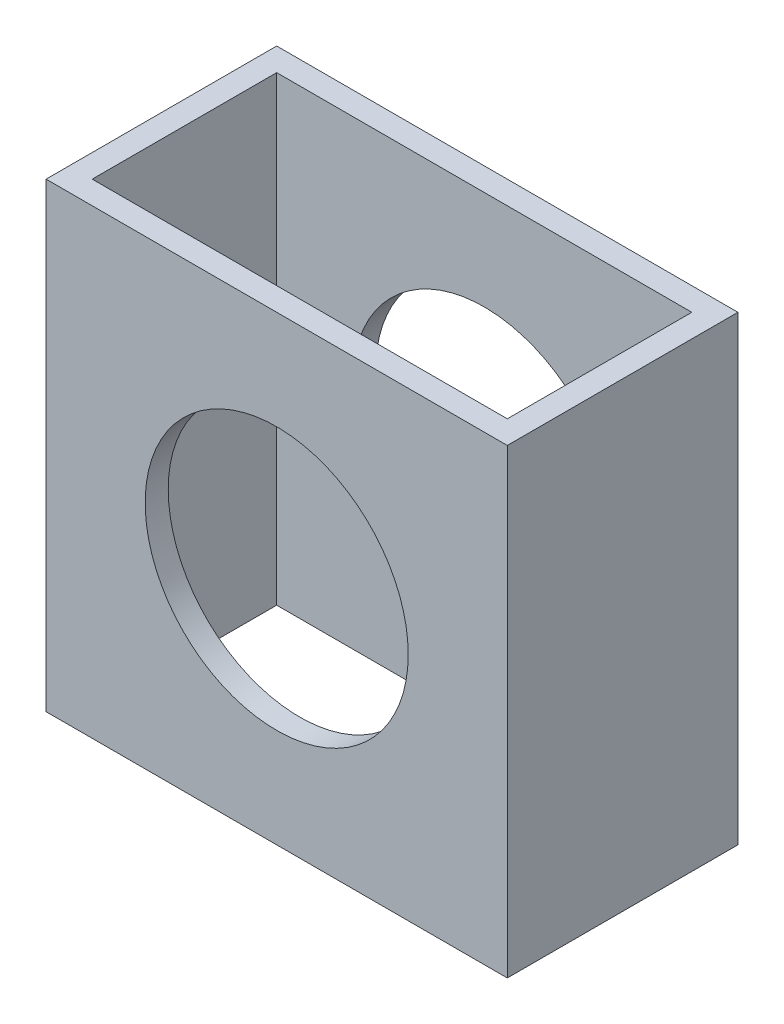
SolidWorks part; units mm, degrees
ref_plane "Front Plane" through (0, 0, 0) normal (0, 0, 1) x (1, 0, 0)
ref_plane "Top Plane" through (0, 0, 0) normal (0, 1, 0) x (1, 0, 0)
ref_plane "Right Plane" through (0, 0, 0) normal (1, 0, 0) x (0, 0, -1)
sketch "Sketch1" plane through (0, 0, 0) normal (1, 0, 0) x (0, 0, -1)
  line L0 (0, 0) -> (0, 50.8)
  dimension "D1" = 50.8
other "Rectangular tube 2IN X 1IN(1)"
ref_plane "Plane1" through (-25.4, 0, -12.7) normal (0, 1, 0) x (0, 0, 1)
sketch "Sketch12" plane through (-25.4, 0, -12.7) normal (0, 1, 0) x (0, 0, 1)
  line L0 (0, 0) -> (0, 50.8)
  line L1 (0, 50.8) -> (25.4, 50.8)
  line L2 (0, 0) -> (25.4, 0)
  line L3 (25.4, 50.8) -> (25.4, 0)
  line L4 (2.54, 48.26) -> (22.86, 48.26)
  line L5 (22.86, 48.26) -> (22.86, 2.54)
  line L6 (2.54, 2.54) -> (22.86, 2.54)
  line L7 (2.54, 2.54) -> (2.54, 48.26)
  line L8 (0, 0) -> (25.4, 50.8) construction
  point P0 (0, 0)
  point P2 (0, 25.4)
  point P4 (0, 0)
  point P6 (12.7, 0)
  point P7 (0, 25.4)
  point P8 (25.4, 25.4)
  point P9 (25.4, 0)
  point P10 (12.7, 50.8)
  point P11 (25.4, 50.8)
  point P12 (0, 50.8)
  point P16 (0, 0)
  point P17 (0, 0)
  point P19 (12.7, 25.4)
  point P20 (25.4, 0)
  point P23 (25.4, 50.8)
  point P26 (0, 50.8)
  dimension "D2" = 25.4
  dimension "D3" = 2.54
  dimension "D1" = 50.8
hole_wizard "1-1/8 Clearance Hole1" positions "Sketch13" profile "Sketch14" hole size "1-1/8" standard "ANSI Inch" end condition through all
sketch "Sketch13" plane through (0, 0, 12.7) normal (0, 0, 1) x (1, 0, 0)
  line L0 (-25.4, 0) -> (25.4, 50.8) construction
  point P0 (0, 25.4)
  point P9 (0, 0)
sketch "Sketch14" plane through (0, 25.4, 12.7) normal (1, 0, 0) x (0, -1, 0)
  line L0 (0, 0) -> (0, 25.4)
  line L1 (0, 25.4) -> (14.4856, 25.4)
  line L2 (14.4856, 25.4) -> (14.4856, 0)
  line L5 (14.4856, 0) -> (0, 0)
  line L11 (0, -6.35) -> (0, 107.95) construction
  dimension "Thru Hole Dia." = 28.9712
  dimension "Thru Hole Depth" = 25.4
